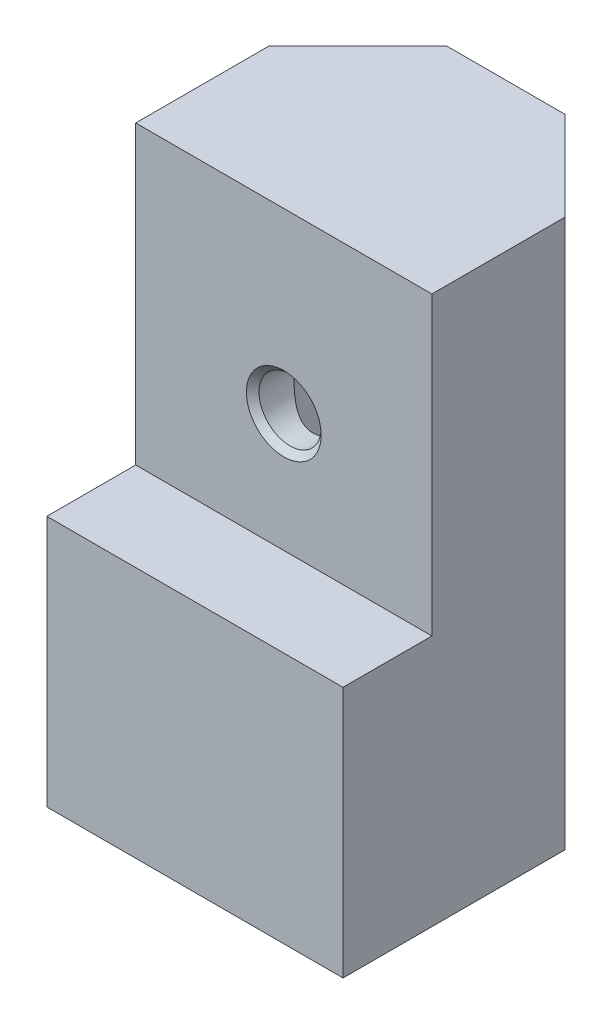
SolidWorks part; units mm, degrees
ref_plane "Front" through (0, 0, 0) normal (0, 0, 1) x (1, 0, 0)
ref_plane "Top" through (0, 0, 0) normal (0, 1, 0) x (1, 0, 0)
ref_plane "Right" through (0, 0, 0) normal (1, 0, 0) x (0, 0, -1)
sketch "Sketch1" plane through (0, 0, 0) normal (0, 0, 1) x (1, 0, 0)
  line L0 (-10, 8.5) -> (0, 0) construction
  line L1 (-10, 8.5) -> (10, 8.5)
  line L2 (-10, 8.5) -> (-10, -8.5)
  line L3 (-10, -8.5) -> (10, -8.5)
  line L4 (10, 8.5) -> (10, -8.5)
  line L5 (0, 0) -> (10, -8.5) construction
  dimension "D1" = 17
  dimension "D2" = 20
extrude "Boss-Extrude1" add sketch "Sketch1" along normal blind 6
sketch "Sketch2" plane through (0, 0, 0) normal (0, 0, -1) x (-1, 0, 0)
  line L0 (10, 8.5) -> (10, -8.5) construction
  line L1 (-10, -8.5) -> (10, -8.5)
  line L2 (-10, -8.5) -> (-10, 28.5)
  line L3 (-10, 28.5) -> (10, 28.5)
  line L4 (10, -8.5) -> (10, 28.5)
  dimension "D1" = 37
extrude "Boss-Extrude2" add sketch "Sketch2" along normal blind 15
hole_wizard "M5 Tapped Hole1" positions "3DSketch1" profile "Sketch4" tap size "M5" standard "ISO"
sketch3d "3DSketch1"
  line L0 (10, 8.5, 0) -> (-10, 8.5, 0) construction
  point P0 (0, 16.5, 0)
  point P5 (0, 8.5, 0)
  dimension "D1" = 8
cosmetic thread "Hole Thread1" parameters "D1"=7.4, "D2"=5
sketch "Sketch4" plane through (0, 16.5, 0) normal (1, 0, 0) x (0, -1, 0)
  line L0 (0, 0) -> (0, 11.0618)
  line L1 (0, 11.0618) -> (2.1, 9.8)
  line L2 (2.1, 9.8) -> (2.1, 0.425)
  line L3 (2.1, 0.425) -> (2.525, 0)
  line L5 (2.525, 0) -> (0, 0)
  line L6 (-2.1, 0.425) -> (-2.525, 0) construction
  line L10 (0, 11.0618) -> (-2.1, 9.8) construction
  line L11 (0, -6.35) -> (0, 107.95) construction
  dimension "Tap Drill Dia." = 4.2
  dimension "Tap Drill Depth" = 9.8
  dimension "Near C'Sink Dia." = 5.05
  dimension "Near C'Sink Angle" = 90
  dimension "Drill Angle" = 118
sketch "Sketch5" plane through (0, -8.5, 0) normal (0, -1, 0) x (1, 0, 0)
  line L0 (10, -15) -> (-10, -15) construction
  circle A0 centre (0, -5) radius 3.05
  dimension "D2" = 6.1
  dimension "D1" = 10
extrude "Cut-Extrude1" cut sketch "Sketch5" against normal blind 25
chamfer "Chamfer1" distance 6 angle 45 2 edges at (-10, 10, -15) (10, 10, -15)
